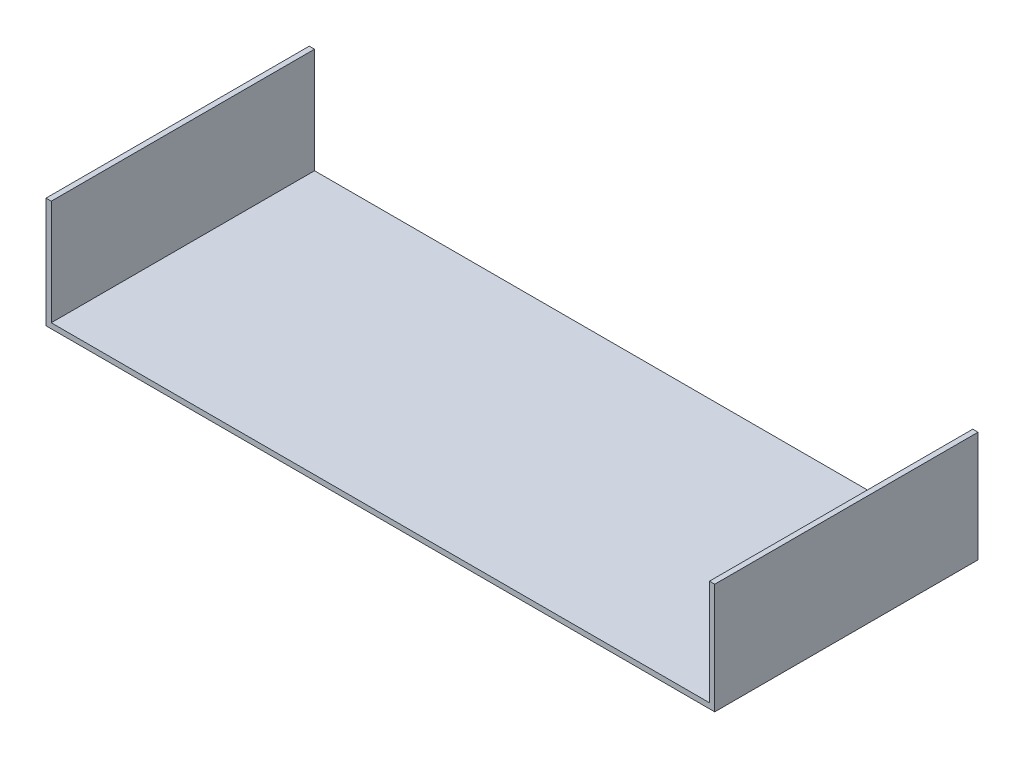
SolidWorks part; units mm, degrees
ref_plane "Front Plane" through (0, 0, 0) normal (0, 0, 1) x (1, 0, 0)
ref_plane "Top Plane" through (0, 0, 0) normal (0, 1, 0) x (1, 0, 0)
ref_plane "Right Plane" through (0, 0, 0) normal (1, 0, 0) x (0, 0, -1)
sketch "Sketch1" plane through (0, 0, 0) normal (0, 0, 1) x (1, 0, 0)
  line L0 (0, 0) -> (0, -4000)
  line L1 (0, -4000) -> (25000, -4000)
  line L2 (25000, -4000) -> (25000, 0)
  line L3 (-200, 0) -> (-200, -4200)
  line L4 (-200, -4200) -> (25200, -4200)
  line L5 (25200, -4200) -> (25200, 0)
  line L6 (-200, 0) -> (0, 0)
  line L7 (25000, 0) -> (25200, 0)
extrude "Boss-Extrude1" add sketch "Sketch1" along normal blind 10000
